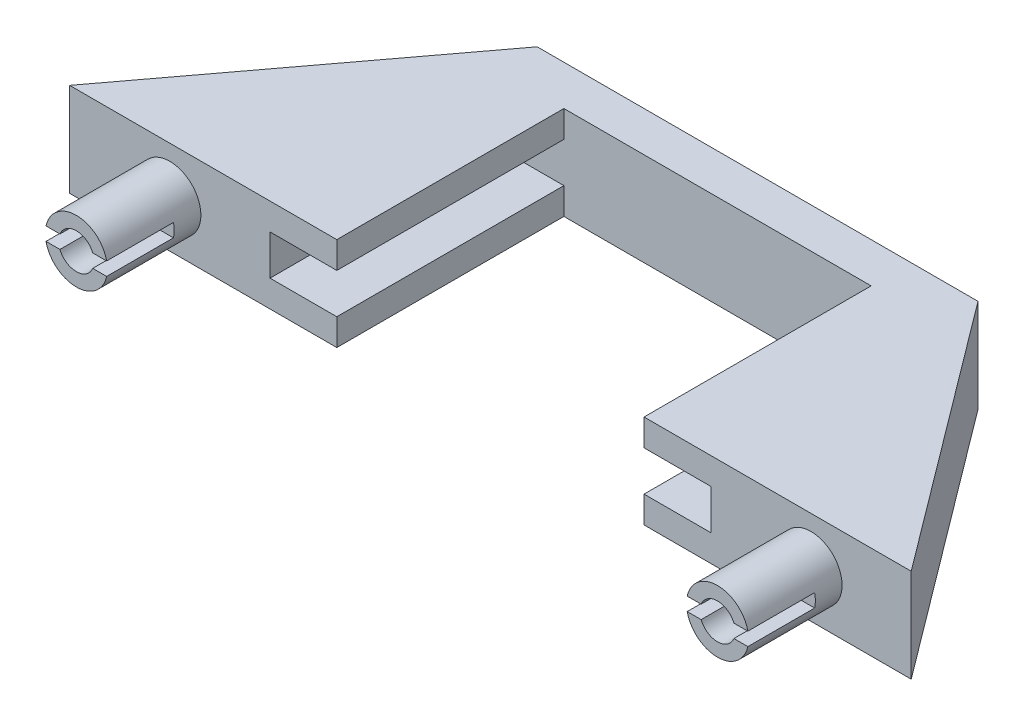
SolidWorks part; units mm, degrees
ref_plane "Front Plane" through (0, 0, 0) normal (0, 0, 1) x (1, 0, 0)
ref_plane "Top Plane" through (0, 0, 0) normal (0, 1, 0) x (1, 0, 0)
ref_plane "Right Plane" through (0, 0, 0) normal (1, 0, 0) x (0, 0, -1)
sketch "Sketch1" plane through (0, 0, 0) normal (0, 0, 1) x (1, 0, 0)
  line L1 (-16.5, 3.5) -> (16.5, 3.5)
  line L2 (-16.5, 3.5) -> (-16.5, -3.5)
  line L3 (-16.5, -3.5) -> (16.5, -3.5)
  line L4 (16.5, 3.5) -> (16.5, -3.5)
  line L5 (-16.5, 3.5) -> (16.5, -3.5) construction
  line L6 (-16.5, -3.5) -> (16.5, 3.5) construction
  point P0 (0, 0)
  dimension "D1" = 33
  dimension "D2" = 7
extrude "Boss-Extrude1" add sketch "Sketch1" along normal blind 3
sketch "Sketch2" plane through (0, 0, 3) normal (0, 0, 1) x (1, 0, 0)
  line L1 (-16.5, 3.5) -> (-11.5, 3.5)
  line L2 (-16.5, 3.5) -> (-16.5, 1.5)
  line L3 (-16.5, 1.5) -> (-11.5, 1.5)
  line L4 (-11.5, 3.5) -> (-11.5, 1.5)
  line L5 (-16.5, -3.5) -> (-11.5, -3.5)
  line L6 (-16.5, -3.5) -> (-16.5, -1.5)
  line L7 (-16.5, -1.5) -> (-11.5, -1.5)
  line L8 (-11.5, -3.5) -> (-11.5, -1.5)
  line L9 (16.5, -3.5) -> (11.5, -3.5)
  line L10 (16.5, -3.5) -> (16.5, -1.5)
  line L11 (16.5, -1.5) -> (11.5, -1.5)
  line L12 (11.5, -3.5) -> (11.5, -1.5)
  line L13 (16.5, 3.5) -> (11.5, 3.5)
  line L14 (16.5, 3.5) -> (16.5, 1.5)
  line L15 (16.5, 1.5) -> (11.5, 1.5)
  line L16 (11.5, 3.5) -> (11.5, 1.5)
  dimension "D1" = 2
  dimension "D2" = 5
  dimension "D3" = 2
  dimension "D4" = 5
extrude "Boss-Extrude2" add sketch "Sketch2" along normal blind 17
sketch "Sketch3" plane through (0, 3.5, 0) normal (0, 1, 0) x (1, 0, 0)
  line L0 (-16.5, -20) -> (-31.5, -20)
  line L1 (-31.5, -20) -> (-16.5, 0)
  line L2 (-16.5, -20) -> (-16.5, 0)
  line L3 (16.5, -20) -> (31.5, -20)
  line L4 (31.5, -20) -> (16.5, 0)
  line L5 (16.5, -20) -> (16.5, 0)
  dimension "D1" = 25
  dimension "D2" = 15
  dimension "D3" = 15
extrude "Boss-Extrude3" add sketch "Sketch3" against normal blind 7
sketch "Sketch4" plane through (0, 0, 20) normal (0, 0, 1) x (1, 0, 0)
  line L0 (16.5, -1.5) -> (16.5, -3.5) construction
  line L1 (16.5, -3.5) -> (16.5, 3.5) construction
  line L2 (16.5, 3.5) -> (31.5, -3.5) construction
  line L3 (31.5, -3.5) -> (31.5, 3.5) construction
  line L4 (31.5, 3.5) -> (16.5, -3.5) construction
  line L5 (-16.5, -1.5) -> (-16.5, 3.5) construction
  line L6 (-16.5, 3.5) -> (-16.5, -3.5) construction
  line L7 (-16.5, -3.5) -> (-31.5, 3.5) construction
  line L8 (-31.5, -3.5) -> (-31.5, 3.5) construction
  line L9 (-11.5, 3.5) -> (-31.5, 3.5) construction
  line L10 (-31.5, 3.5) -> (-31.5, -3.5) construction
  line L11 (-31.5, -3.5) -> (-16.5, 3.5) construction
  circle A0 centre (24, 0) radius 2.325
  circle A1 centre (-24, 0) radius 2.325
  dimension "D1" = 4.65
  dimension "D2" = 4.65
extrude "Boss-Extrude4" add sketch "Sketch4" along normal blind 7
sketch "Sketch5" plane through (0, 0, 27) normal (0, 0, 1) x (1, 0, 0)
  circle A0 centre (-24, 0) radius 1.325
  circle A1 centre (24, 0) radius 1.325
  dimension "D1" = 2.65
  dimension "D2" = 2.65
extrude "Cut-Extrude1" cut sketch "Sketch5" against normal blind 7
sketch "Sketch6" plane through (0, 0, 27) normal (0, 0, 1) x (1, 0, 0)
  line L1 (-31.1574, 0.5) -> (-21.4926, 0.5)
  line L2 (-31.1574, 0.5) -> (-31.1574, -0.5)
  line L3 (-31.1574, -0.5) -> (-21.4926, -0.5)
  line L4 (-21.4926, 0.5) -> (-21.4926, -0.5)
  line L5 (-31.1574, 0.5) -> (-21.4926, -0.5) construction
  line L6 (-31.1574, -0.5) -> (-21.4926, 0.5) construction
  line L7 (31.4066, 0.5) -> (21.2434, 0.5)
  line L8 (31.4066, 0.5) -> (31.4066, -0.5)
  line L9 (31.4066, -0.5) -> (21.2434, -0.5)
  line L10 (21.2434, 0.5) -> (21.2434, -0.5)
  line L11 (31.4066, 0.5) -> (21.2434, -0.5) construction
  line L12 (31.4066, -0.5) -> (21.2434, 0.5) construction
  circle A0 centre (-24, 0) radius 2.325 construction
  circle A1 centre (-24, 0) radius 2.325 construction
  circle A2 centre (24, 0) radius 2.325 construction
  circle A3 centre (24, 0) radius 2.325 construction
  point P0 (-26.325, 0)
  point P9 (26.325, 0)
  dimension "D1" = 1
  dimension "D2" = 1
extrude "Cut-Extrude2" cut sketch "Sketch6" against normal blind 5
